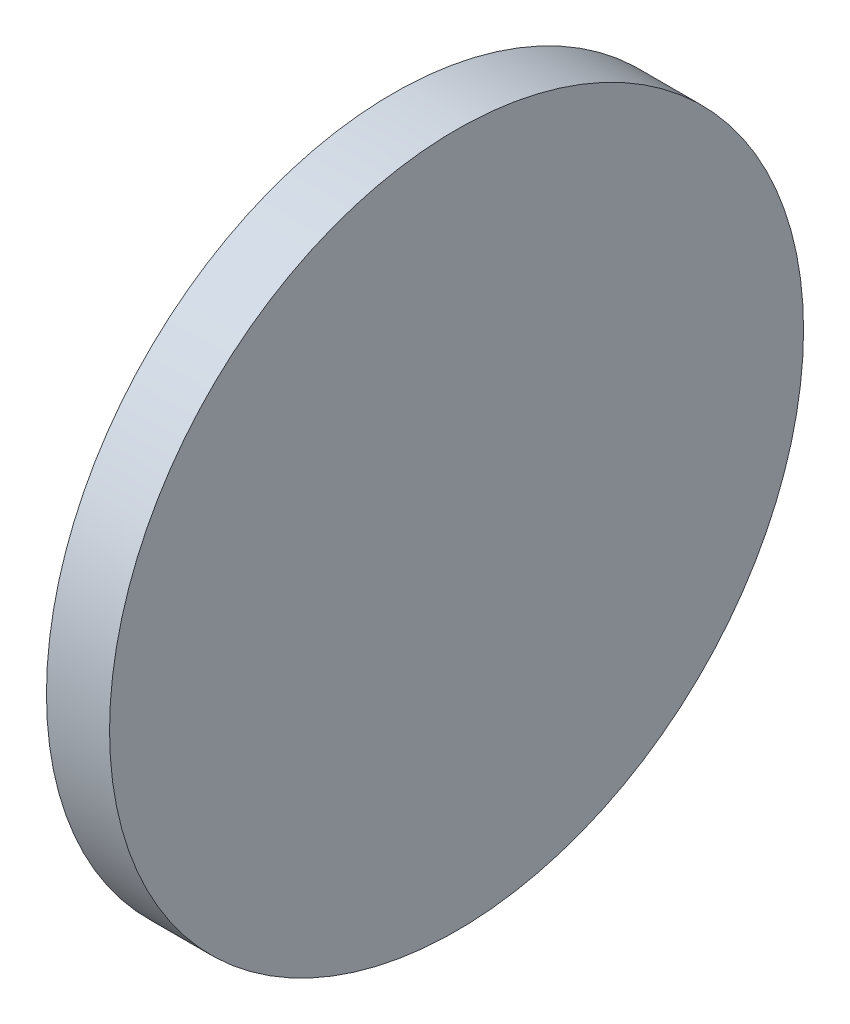
SolidWorks part; units mm, degrees
ref_plane "Front Plane" through (0, 0, 0) normal (0, 0, 1) x (1, 0, 0)
ref_plane "Top Plane" through (0, 0, 0) normal (0, 1, 0) x (1, 0, 0)
ref_plane "Right Plane" through (0, 0, 0) normal (1, 0, 0) x (0, 0, -1)
sketch "Sketch1" plane through (0, 0, 0) normal (1, 0, 0) x (0, 0, -1)
  circle A0 centre (0, 0) radius 110
  dimension "D1" = 220
extrude "Boss-Extrude1" add sketch "Sketch1" along normal blind 20
